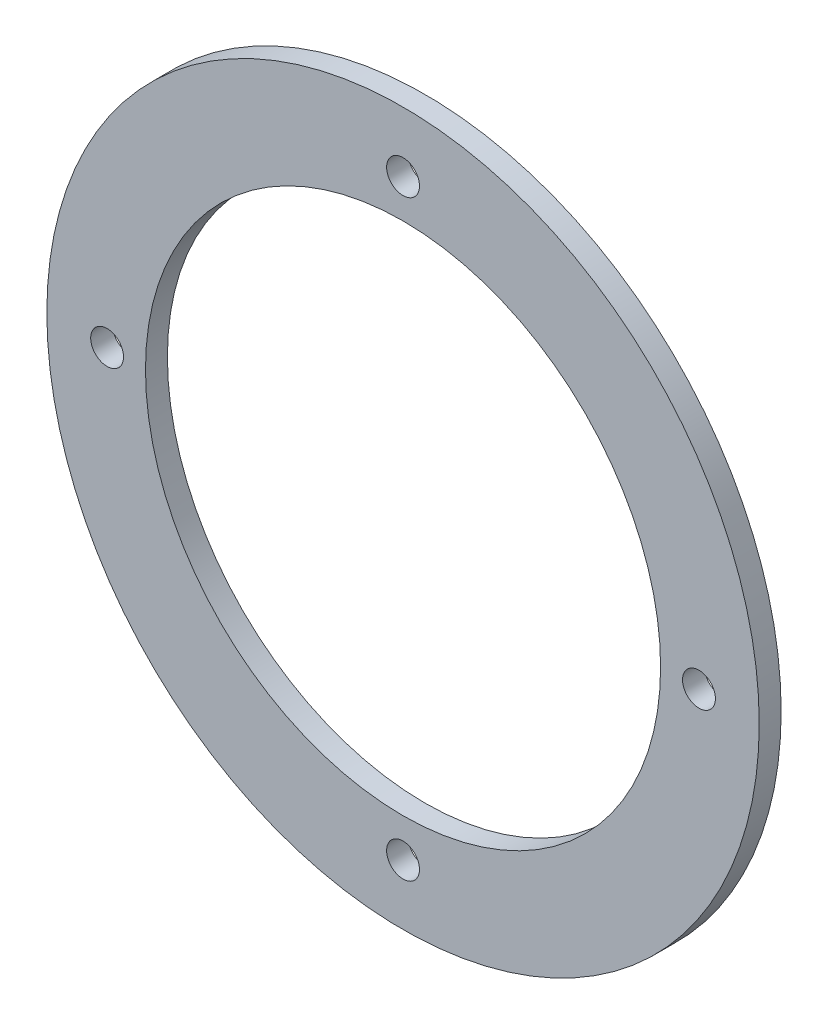
SolidWorks part; units mm, degrees
ref_plane "Front Plane" through (0, 0, 0) normal (0, 0, 1) x (1, 0, 0)
ref_plane "Top Plane" through (0, 0, 0) normal (0, 1, 0) x (1, 0, 0)
ref_plane "Right Plane" through (0, 0, 0) normal (1, 0, 0) x (0, 0, -1)
sketch "Sketch1" plane through (0, 0, 0) normal (0, 0, 1) x (1, 0, 0)
  circle A0 centre (0, 0) radius 32.5
  circle A1 centre (0, 0) radius 23.5
  circle A2 centre (-27, 0) radius 1.5
  circle A3 centre (27, 0) radius 1.5
  circle A4 centre (0, 27) radius 1.5
  circle A5 centre (0, -27) radius 1.5
  dimension "D1" = 65
  dimension "D2" = 47
  dimension "D3" = 3
  dimension "D4" = 3
  dimension "D5" = 3
  dimension "D6" = 3
  dimension "D7" = 27
  dimension "D8" = 27
  dimension "D9" = 27
  dimension "D10" = 27
extrude "Boss-Extrude1" add sketch "Sketch1" along normal blind 2
